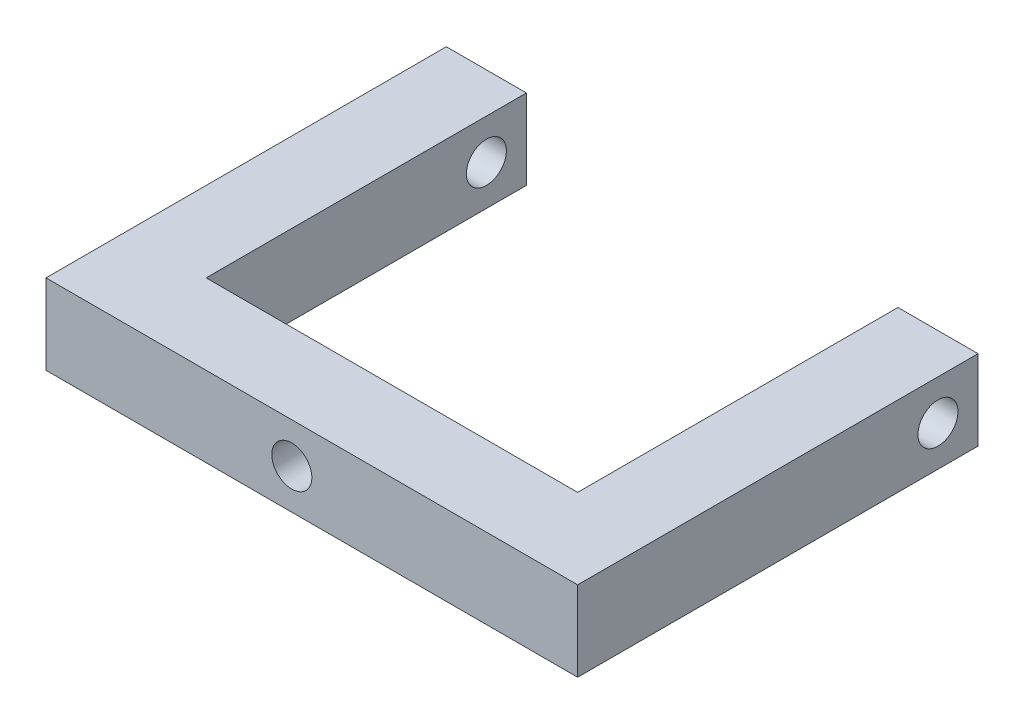
SolidWorks part; units mm, degrees
ref_plane "Front Plane" through (0, 0, 0) normal (0, 0, 1) x (1, 0, 0)
ref_plane "Top Plane" through (0, 0, 0) normal (0, 1, 0) x (1, 0, 0)
ref_plane "Right Plane" through (0, 0, 0) normal (1, 0, 0) x (0, 0, -1)
sketch "Sketch1" plane through (0, 0, 0) normal (0, 1, 0) x (1, 0, 0)
  line L0 (0, 0) -> (-84.328, 0)
  line L3 (-12.7, 12.7) -> (-71.628, 12.7)
  line L6 (-71.628, 12.7) -> (-71.628, 63.5)
  line L7 (-71.628, 63.5) -> (-84.328, 63.5)
  line L8 (-84.328, 0) -> (-84.328, 63.5)
  line L10 (-12.7, 12.7) -> (-12.7, 63.5)
  line L11 (-12.7, 63.5) -> (0, 63.5)
  line L12 (0, 0) -> (0, 63.5)
  point P0 (0, 0)
  dimension "D1" = 12.7
  dimension "D2" = 58.928
  dimension "D3" = 12.7
  dimension "D4" = 50.8
  dimension "D5" = 12.7
extrude "Boss-Extrude1" add sketch "Sketch1" along normal blind 12.7 contours L8 L7 L6 L3 L10 L11 L12 L0
sketch "Sketch2" plane through (0, 0, 0) normal (1, 0, 0) x (0, 0, -1)
  line L0 (0, 12.7) -> (63.5, 12.7) construction
  line L1 (63.5, 12.7) -> (63.5, 0) construction
  circle A0 centre (57.15, 6.35) radius 3.175
  dimension "D1" = 6.35
  dimension "D2" = 6.35
extrude "Cut-Extrude1" cut sketch "Sketch2" against normal up to surface (84.328 mm away) up to face at (-84.328, 6.35, -31.75)
sketch "Sketch3" plane through (0, 0, -12.7) normal (0, 0, -1) x (-1, 0, 0)
  line L0 (71.628, 12.7) -> (71.628, 0) construction
  line L1 (12.7, 0) -> (71.628, 0) construction
  circle A0 centre (45.339, 6.35) radius 3.175
  dimension "D1" = 6.35
  dimension "D2" = 26.289
  dimension "D3" = 6.35
extrude "Cut-Extrude2" cut sketch "Sketch3" against normal up to surface (12.7 mm away) up to face at (-42.164, 6.35, 0)
